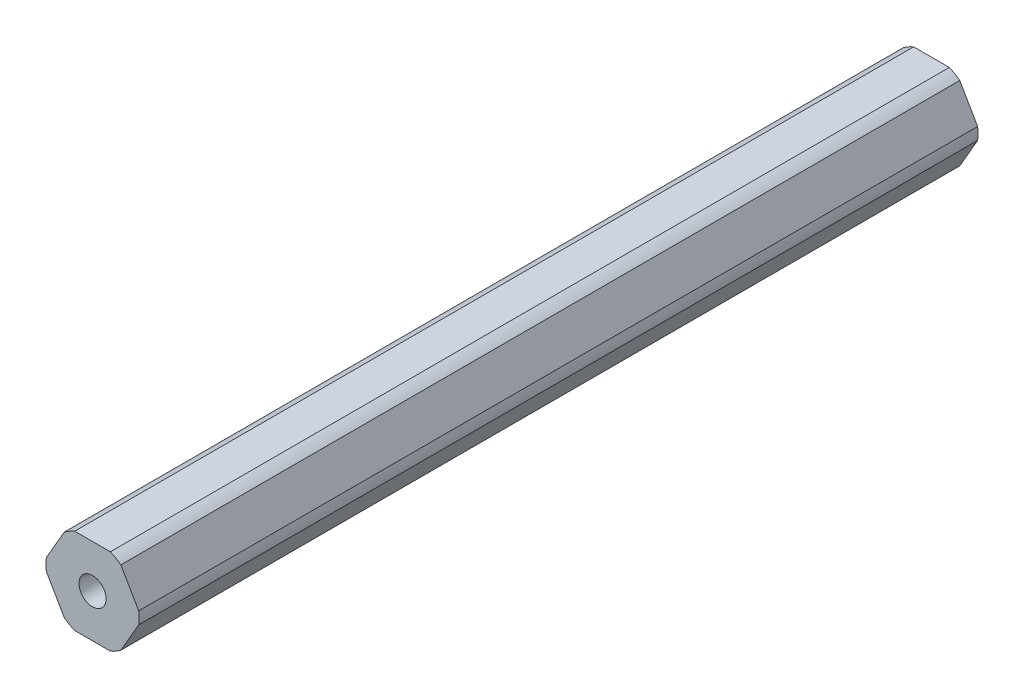
SolidWorks part; units mm, degrees
material "6061-T6 (SS)"
ref_plane "Front Plane" through (0, 0, 0) normal (0, 0, 1) x (1, 0, 0)
ref_plane "Top Plane" through (0, 0, 0) normal (0, 1, 0) x (1, 0, 0)
ref_plane "Right Plane" through (0, 0, 0) normal (1, 0, 0) x (0, 0, -1)
sketch "Sketch1" plane through (0, 0, 0) normal (0, 0, 1) x (1, 0, 0)
  line L1 (3.6662, 6.35) -> (-3.6662, 6.35)
  line L2 (-3.6662, 6.35) -> (-7.3323, 0)
  line L3 (-7.3323, 0) -> (-3.6662, -6.35)
  line L4 (-3.6662, -6.35) -> (3.6662, -6.35)
  line L5 (3.6662, -6.35) -> (7.3323, 0)
  line L6 (7.3323, 0) -> (3.6662, 6.35)
  circle A0 centre (0, 0) radius 6.35 construction
  circle A1 centre (0, 0) radius 2
  circle A2 centre (0, 0) radius 6.875
  point P1 (0, 6.35)
  dimension "D2" = 13.75
  dimension "D3" = 4
  dimension "D1" = 12.7
extrude "Boss-Extrude1" add sketch "Sketch1" along normal mid plane 123.825 contours L6 A2 L1 L2 L3 L4 L5 A1
sketch "Sketch4" plane through (0, 0, 61.9125) normal (0, 0, 1) x (1, 0, 0)
  circle A0 centre (0, 0) radius 6.35
  circle A2 centre (0, 0) radius 2.4892
  dimension "D1" = 12.7
  dimension "D2" = 4.9784
equation "\"D2@Sketch1\"=13.75mm"
equation "\"D3@Sketch1\"=4mm"
